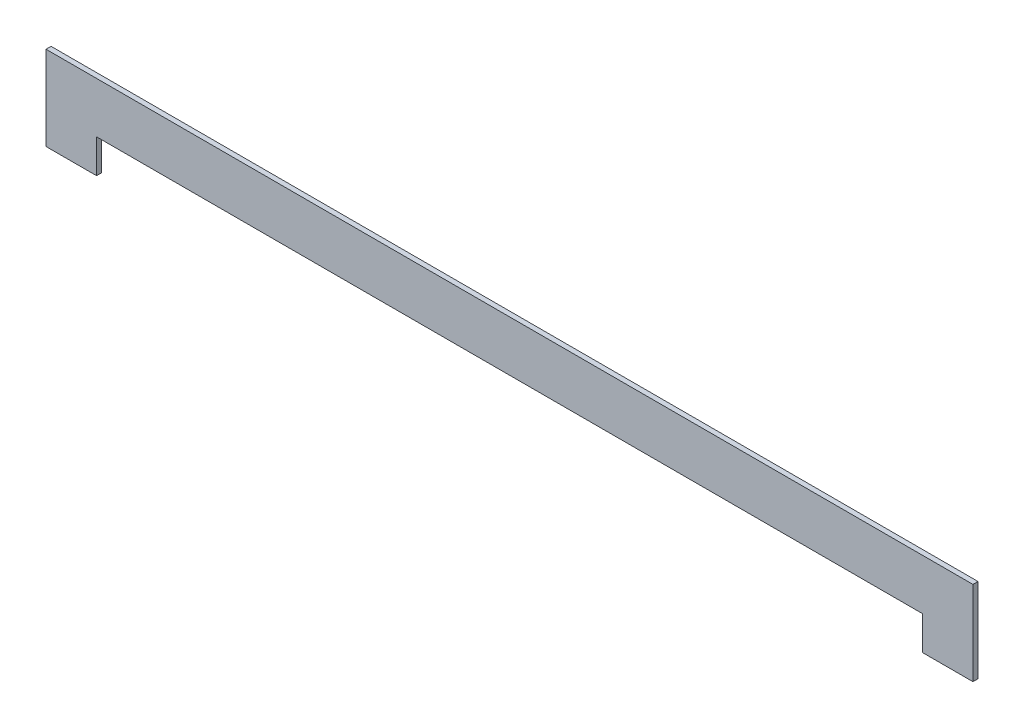
SolidWorks part; units mm, degrees
ref_plane "前视基准面" through (0, 0, 0) normal (0, 0, 1) x (1, 0, 0)
ref_plane "上视基准面" through (0, 0, 0) normal (0, 1, 0) x (1, 0, 0)
ref_plane "右视基准面" through (0, 0, 0) normal (1, 0, 0) x (0, 0, -1)
sketch "草图1" plane through (0, 0, 0) normal (0, 0, 1) x (1, 0, 0)
  line L1 (-275, 25) -> (275, 25)
  line L2 (-275, 25) -> (-275, -25)
  line L3 (-275, -25) -> (275, -25)
  line L4 (275, 25) -> (275, -25)
  point P4 (0, 25)
  point P6 (275, 0)
  dimension "D1" = 550
  dimension "D2" = 50
extrude "凸台-拉伸1" add sketch "草图1" along normal blind 3
sketch "草图2" plane through (0, 0, 0) normal (0, 0, 1) x (1, 0, 0)
  line L0 (-275, -25) -> (275, -25) construction
  line L1 (-245, -25) -> (245, -25)
  line L2 (-245, -25) -> (-245, -5)
  line L3 (-245, -5) -> (245, -5)
  line L4 (245, -25) -> (245, -5)
  line L5 (0, 25) -> (0, -25) construction
  line L6 (275, 25) -> (-275, 25) construction
  line L7 (-275, 25) -> (-275, -25) construction
  dimension "D1" = 30
  dimension "D2" = 30
extrude "切除-拉伸2" cut sketch "草图2" along normal blind 3
sketch "草图3" plane through (0, 0, 0) normal (1, 0, 0) x (0, 0, -1)
  line L0 (-3, -25) -> (0, -22)
  line L1 (0, -25) -> (0, 25) construction
  line L2 (0, -22) -> (0, -25)
  line L3 (0, -25) -> (-3, -25)
  dimension "D1" = 3
